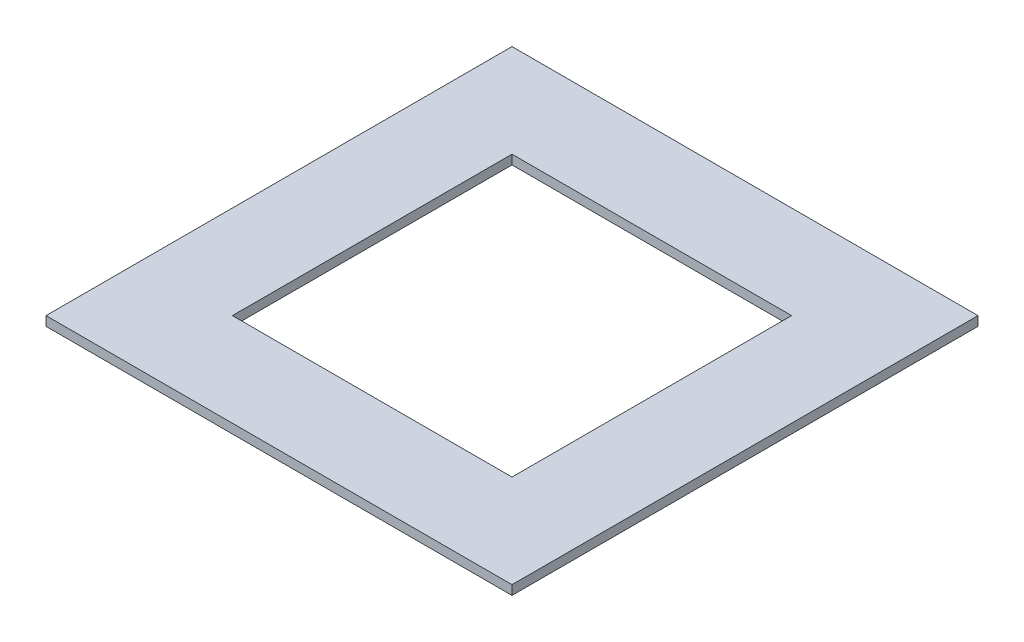
SolidWorks part; units mm, degrees
ref_plane "Alzado" through (0, 0, 0) normal (0, 0, 1) x (1, 0, 0)
ref_plane "Planta" through (0, 0, 0) normal (0, 1, 0) x (1, 0, 0)
ref_plane "Vista lateral" through (0, 0, 0) normal (1, 0, 0) x (0, 0, -1)
sketch "Croquis1" plane through (0, 0, 0) normal (0, 1, 0) x (1, 0, 0)
  line L0 (0, 0) -> (25, 25) construction
  line L1 (0, 0) -> (25, 0)
  line L2 (0, 0) -> (0, 25)
  line L3 (0, 25) -> (25, 25)
  line L4 (25, 0) -> (25, 25)
  line L5 (5, 20) -> (20, 5) construction
  line L6 (5, 5) -> (20, 5)
  line L7 (5, 5) -> (5, 20)
  line L8 (5, 20) -> (20, 20)
  line L9 (20, 5) -> (20, 20)
  point P9 (12.5, 12.5)
  dimension "D1" = 25
  dimension "D2" = 15
extrude "Saliente-Extruir1" add sketch "Croquis1" along normal blind 0.5
